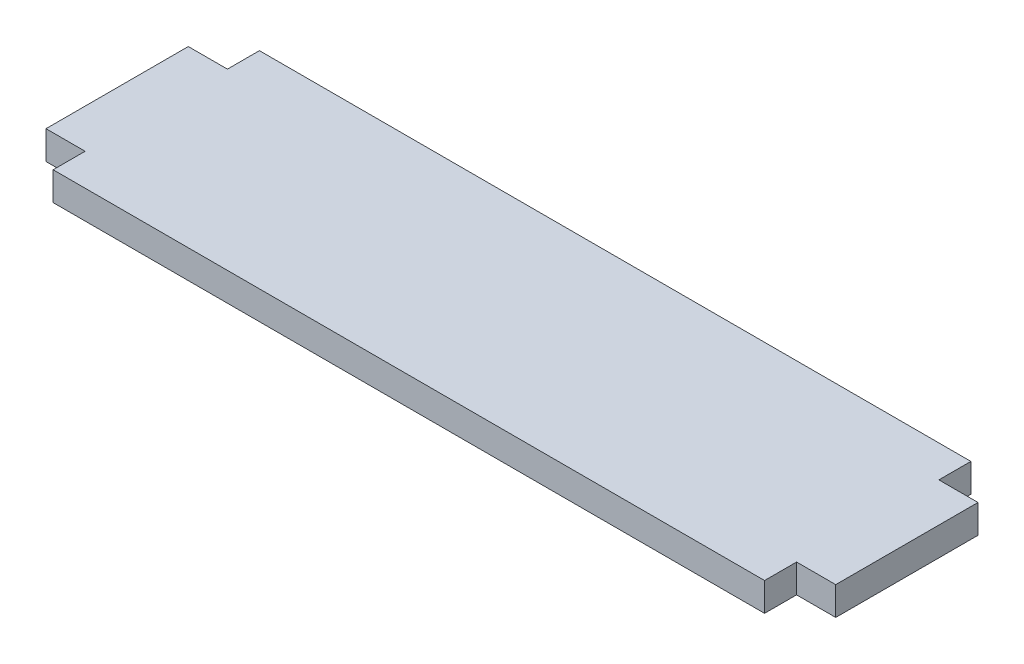
SolidWorks part; units mm, degrees
ref_plane "Спереди" through (0, 0, 0) normal (0, 0, 1) x (1, 0, 0)
ref_plane "Сверху" through (0, 0, 0) normal (0, 1, 0) x (1, 0, 0)
ref_plane "Справа" through (0, 0, 0) normal (1, 0, 0) x (0, 0, -1)
sketch "Эскиз1" plane through (0, 0, 0) normal (0, 1, 0) x (1, 0, 0)
  line L1 (-50, -14.4985) -> (50, -14.4985)
  line L2 (-50, -14.4985) -> (-50, 14.4985)
  line L3 (-50, 14.4985) -> (50, 14.4985)
  line L4 (50, -14.4985) -> (50, 14.4985)
  line L5 (-50, -14.4985) -> (50, 14.4985) construction
  line L6 (-50, 14.4985) -> (50, -14.4985) construction
  point P0 (0, 0)
  dimension "D1" = 28.997
  dimension "D2" = 100
extrude "Бобышка-Вытянуть1" add sketch "Эскиз1" along normal blind 4
sketch "Эскиз2" plane through (50, 0, 0) normal (1, 0, 0) x (0, 0, -1)
  line L0 (14.4985, 4) -> (-14.4985, 0) construction
  line L2 (-10, 4) -> (10, 4)
  line L3 (-10, 4) -> (-10, 0)
  line L4 (-10, 0) -> (10, 0)
  line L5 (10, 4) -> (10, 0)
  line L6 (-10, 4) -> (10, 0) construction
  line L7 (-10, 0) -> (10, 4) construction
  point P4 (0, 2)
  dimension "D1" = 4
  dimension "D2" = 20
extrude "Бобышка-Вытянуть2" add sketch "Эскиз2" along normal blind 5.5
mirror "Mirror1" about plane through (0, 0, 0) normal (1, 0, 0) of "Бобышка-Вытянуть2"
